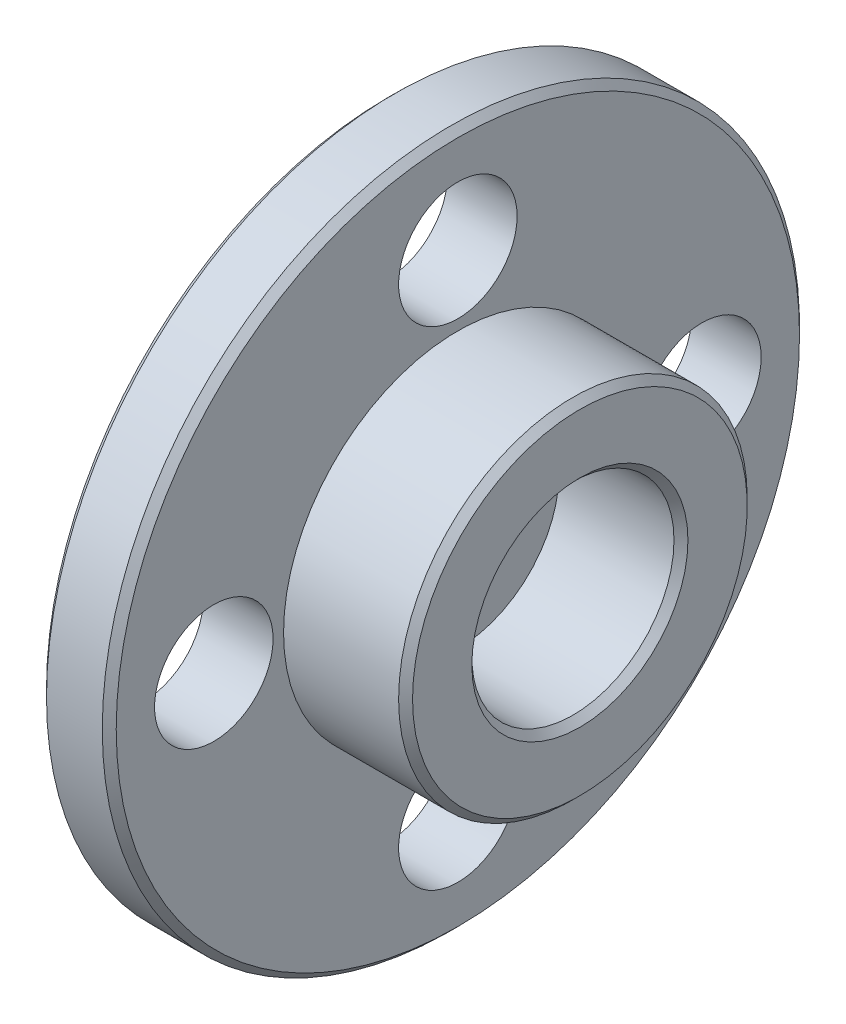
SolidWorks part; units mm, degrees
material "Q235"
ref_plane "前视基准面" through (0, 0, 0) normal (0, 0, 1) x (1, 0, 0)
ref_plane "上视基准面" through (0, 0, 0) normal (0, 1, 0) x (1, 0, 0)
ref_plane "右视基准面" through (0, 0, 0) normal (1, 0, 0) x (0, 0, -1)
sketch "草图1" plane through (0, 0, 0) normal (0, 0, 1) x (1, 0, 0)
  line L0 (0, 0) -> (9.067, 0) construction
  line L1 (0, 0) -> (0, 10)
  line L2 (0, 10) -> (2, 10)
  line L3 (2, 10) -> (2, 5)
  line L4 (2, 5) -> (5.5, 5)
  line L5 (5.5, 5) -> (5.5, 0)
  line L6 (5.5, 0) -> (0, 0)
  dimension "D1" = 2
  dimension "D2" = 5.5
  dimension "D3" = 20
  dimension "D4" = 10
revolve "旋转1" add sketch "草图1" angle 360 about L0
sketch "草图2" plane through (5.5, 0, 0) normal (1, 0, 0) x (0, 0, -1)
  circle A0 centre (0, 0) radius 2.9
  dimension "D1" = 5.8
extrude "切除-拉伸1" cut sketch "草图2" against normal blind 3.5
sketch "草图3" plane through (0, 0, 0) normal (-1, 0, 0) x (0, 0, 1)
  circle A0 centre (0, 0) radius 1.5
  dimension "D1" = 3
extrude "切除-拉伸2" cut sketch "草图3" against normal up to next
hole_wizard "Ø3.4 (3.4) 直径孔1" positions "草图5" profile "草图4" hole size "Ø3.4" standard "Gb"
sketch "草图5" plane through (2, 0, 0) normal (1, 0, 0) x (0, 0, -1)
  line L0 (0, 7) -> (0, -7) construction
  circle A0 centre (0, 0) radius 7 construction
  point P0 (0, 7)
  point P2 (0, -7)
  point P4 (-7, 0)
  point P6 (7, 0)
  dimension "D1" = 14
sketch "草图4" plane through (2, 7, 0) normal (0, 1, 0) x (0, 0, -1)
  line L0 (0, 0) -> (0, 11.0215)
  line L1 (0, 11.0215) -> (1.7, 10)
  line L2 (1.7, 10) -> (1.7, 0)
  line L5 (1.7, 0) -> (0, 0)
  line L10 (0, 11.0215) -> (-1.7, 10) construction
  line L11 (0, -6.35) -> (0, 107.95) construction
  dimension "孔直径" = 3.4
  dimension "孔深度" = 10
  dimension "导头角度" = 118
chamfer "倒角1" distance 0.2 angle 45 5 edges at (0, 0, 1.5) (5.5, 0, -2.9) (5.5, 0, 5) (0, 0, 10) (2, 0, 10)
